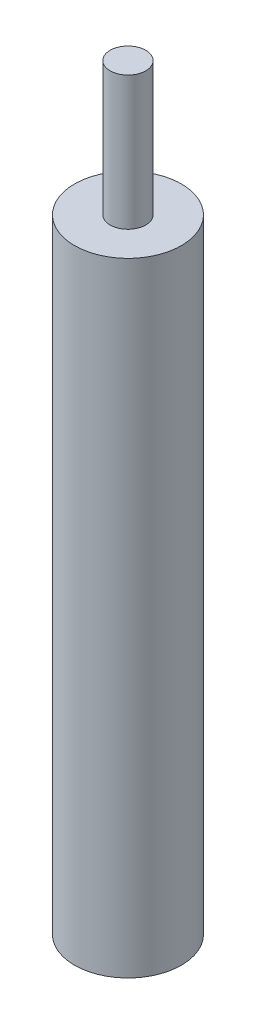
SolidWorks part; units mm, degrees
material "ABS"
ref_plane "Front Plane" through (0, 0, 0) normal (0, 0, 1) x (1, 0, 0)
ref_plane "Top Plane" through (0, 0, 0) normal (0, 1, 0) x (1, 0, 0)
ref_plane "Right Plane" through (0, 0, 0) normal (1, 0, 0) x (0, 0, -1)
other "Configuration Table"
sketch "Sketch1" plane through (0, 0, 0) normal (0, 1, 0) x (1, 0, 0)
  circle A0 centre (0, 0) radius 6
  dimension "D1" = 12
extrude "Probe_Body" add sketch "Sketch1" along normal blind 70
sketch "Sketch2" plane through (0, 0, 0) normal (0, 1, 0) x (1, 0, 0)
  circle A0 centre (-2.5, 0) radius 0.8
  circle A1 centre (2.5, 0) radius 0.8
  dimension "D1" = 1.6
  dimension "D2" = 1.6
extrude "Pin_Wells" cut sketch "Sketch2" along normal blind 3
sketch "Sketch3" plane through (0, 0, 0) normal (0, 1, 0) x (1, 0, 0)
  circle A0 centre (0, 0) radius 2
  dimension "D1" = 4
extrude "Cable_Stub" add sketch "Sketch3" along normal blind 15 from offset 70
equation "\"Jar_OD\"= 90  'ASSUMED - Part G fallback - jar outer diameter"
equation "\"Jar_H\"= 120  'ASSUMED - Part G fallback - jar height"
equation "\"Pump_L\"= 45  'ASSUMED - Part G fallback"
equation "\"Pump_W\"= 24  'ASSUMED - Part G fallback"
equation "\"Pump_H\"= 33  'ASSUMED - Part G fallback"
equation "\"Pump_Outlet_OD\"= 7.5  'ASSUMED - Part G fallback"
equation "\"Tube_OD\"= 8  'ASSUMED - Part G fallback"
equation "\"Tube_ID\"= 6  'ASSUMED - Part G fallback"
equation "\"TDS_Body_Dia\"= 12  'ASSUMED - Part G fallback"
equation "\"TDS_Wet_Len\"= 45  'ASSUMED - Part G fallback - length in water"
equation "\"DS_Tube_Dia\"= 6  'ASSUMED - Part G fallback"
equation "\"DS_Tube_Len\"= 50  'ASSUMED - Part G fallback"
equation "\"ORP_Body_Dia\"= 12  'ASSUMED - Part G fallback"
equation "\"ORP_Body_Len\"= 150  'ASSUMED - Part G fallback"
equation "\"ORP_Cap_Dia\"= 16  'ASSUMED - Part G fallback"
equation "\"Turb_W\"= 33  'ASSUMED - Part G fallback - head width"
equation "\"Turb_D\"= 28  'ASSUMED - Part G fallback - head depth"
equation "\"Turb_H\"= 30  'ASSUMED - Part G fallback - head height"
equation "\"Turb_Slot_W\"= 10  'ASSUMED - Part G fallback - slot width"
equation "\"Flow_L\"= 62  'ASSUMED - Part G fallback YF-S201"
equation "\"Flow_W\"= 36  'ASSUMED - Part G fallback"
equation "\"Flow_H\"= 35  'ASSUMED - Part G fallback"
equation "\"Thread_G12_OD\"= 20.955  'ASSUMED - Part G fallback thread G1/2 (major diameter)"
equation "\"Valve_L\"= 75  'ASSUMED - Part G fallback"
equation "\"Valve_W\"= 45  'ASSUMED - Part G fallback"
equation "\"Valve_H\"= 60  'ASSUMED - Part G fallback"
equation "\"Tee_L\"= 40  'ASSUMED - Part G fallback - overall length"
equation "\"Tee_Branch_L\"= 25  'ASSUMED - Part G fallback"
equation "\"Tee_OD\"= 12  'ASSUMED - Part G fallback"
equation "\"Cuv_W\"= 12.5  'ASSUMED - old R3 cuvette (station suppressed in SS4)"
equation "\"Cuv_D\"= 12.5  'ASSUMED - old R3 cuvette (station suppressed in SS4)"
equation "\"Cuv_H\"= 45  'ASSUMED - old R3 cuvette (station suppressed in SS4)"
equation "\"LED_Board_L\"= 20  'ASSUMED - Part G fallback"
equation "\"LED_Board_W\"= 20  'ASSUMED - Part G fallback - LED at centre"
equation "\"GUVA_L\"= 20  'ASSUMED - Part G fallback"
equation "\"GUVA_W\"= 12  'ASSUMED - Part G fallback - sensor at centre"
equation "\"Reed_L\"= 27  'ASSUMED - Part G fallback MC-38 half"
equation "\"Reed_W\"= 14  'ASSUMED - Part G fallback"
equation "\"Reed_H\"= 8  'ASSUMED - Part G fallback"
equation "\"ESP_L\"= 51  'ASSUMED - Part G fallback"
equation "\"ESP_W\"= 28  'ASSUMED - Part G fallback"
equation "\"TFT_L\"= 58  'ASSUMED - Part G fallback - board"
equation "\"TFT_W\"= 35  'ASSUMED - Part G fallback - board"
equation "\"TFT_Win_L\"= 35  'ASSUMED - Part G fallback - visible window"
equation "\"TFT_Win_W\"= 28  'ASSUMED - Part G fallback - visible window"
equation "\"Relay_L\"= 50  'ASSUMED - Part G fallback"
equation "\"Relay_W\"= 26  'ASSUMED - Part G fallback"
equation "\"Relay_H\"= 19  'ASSUMED - Part G fallback"
equation "\"Mosfet_L\"= 34  'ASSUMED - Part G fallback"
equation "\"Mosfet_W\"= 17  'ASSUMED - Part G fallback"
equation "\"Mosfet_H\"= 12  'ASSUMED - Part G fallback"
equation "\"TDS_Board_L\"= 42  'ASSUMED - Part G fallback"
equation "\"TDS_Board_W\"= 32  'ASSUMED - Part G fallback"
equation "\"Turb_Board_L\"= 38  'ASSUMED - Part G fallback"
equation "\"Turb_Board_W\"= 28  'ASSUMED - Part G fallback"
equation "\"BNC_Thread_Dia\"= 9.5  'ASSUMED - Part G fallback"
equation "\"Plate_L\"= 420  'ASSUMED - Part G fallback"
equation "\"Plate_W\"= 297  'ASSUMED - Part G fallback"
equation "\"Plate_T\"= 6  'ASSUMED - Part G fallback"
equation "\"Probe_Clr\"= 0.3  'DESIGN VALUE - Part C rule 3 - printed probe hole = diameter + 0.3"
equation "\"Cuv_Clr\"= 0.2  'DESIGN VALUE - Part C rule 3 - cuvette pocket = size + 0.2"
equation "\"Label_H\"= 0.6  'DESIGN VALUE - Part D - raised label height"
equation "\"D1@Sketch1\" = \"TDS_Body_Dia\""
equation "\"Booster_L\"= 150  'ASSUMED - Part G fallback - booster pump"
equation "\"Booster_W\"= 95  'ASSUMED - Part G fallback"
equation "\"Booster_H\"= 100  'ASSUMED - Part G fallback"
equation "\"PTube_OD\"= 6.35  'ASSUMED - Part G fallback - product tube 1/4 inch"
equation "\"Qz_Out\"= 12  'ASSUMED - Part G fallback - quartz channel outside square"
equation "\"Qz_Path\"= 10  'ASSUMED - Part G fallback - quartz channel inside light path"
equation "\"Qz_L\"= 40  'ASSUMED - Part G fallback - quartz channel length"
equation "\"LED860_Dia\"= 5  'ASSUMED - Part G fallback - 860 nm LED"
equation "\"BPW_L\"= 5.4  'ASSUMED - Part G fallback - BPW34"
equation "\"BPW_W\"= 4.3  'ASSUMED - Part G fallback - BPW34"
equation "\"Cart_Dia\"= 50  'ASSUMED - Part G fallback - sediment and pre-carbon cartridges"
equation "\"Cart_L\"= 255  'ASSUMED - Part G fallback"
equation "\"UF_Dia\"= 50  'ASSUMED - Part G fallback - UF cartridge"
equation "\"UF_L\"= 260  'ASSUMED - Part G fallback"
equation "\"RO_Dia\"= 62  'ASSUMED - Part G fallback - RO membrane housing"
equation "\"RO_L\"= 300  'ASSUMED - Part G fallback"
equation "\"UVC_Dia\"= 40  'ASSUMED - Part G fallback - UV-C chamber"
equation "\"UVC_L\"= 300  'ASSUMED - Part G fallback"
equation "\"Tank_W\"= 260  'ASSUMED - Part G fallback - storage tank"
equation "\"Tank_D\"= 160  'ASSUMED - Part G fallback"
equation "\"Tank_H\"= 300  'ASSUMED - Part G fallback"
equation "\"Cab_W\"= 400  'ASSUMED - Part G fallback - purifier cabinet"
equation "\"Cab_D\"= 270  'ASSUMED - Part G fallback"
equation "\"Cab_H\"= 560  'ASSUMED - Part G fallback"
equation "\"ORP_Board_L\"= 40  'ASSUMED - Part G fallback - ORP buffer board"
equation "\"ORP_Board_W\"= 30  'ASSUMED - Part G fallback"
equation "\"Opt_Board_L\"= 50  'ASSUMED - Part G fallback - optical front-end board"
equation "\"Opt_Board_W\"= 40  'ASSUMED - Part G fallback"
equation "\"Buck_L\"= 43  'ASSUMED - Part G fallback - 12 V to 5 V buck module"
equation "\"Buck_W\"= 21  'ASSUMED - Part G fallback"
equation "\"Buck_H\"= 14  'ASSUMED - Part G fallback"
equation "\"BB_L\"= 165  'ASSUMED - Part G fallback - breadboard (As_Built_R3 only)"
equation "\"BB_W\"= 55  'ASSUMED - Part G fallback"
equation "\"BB_H\"= 10  'ASSUMED - Part G fallback"
